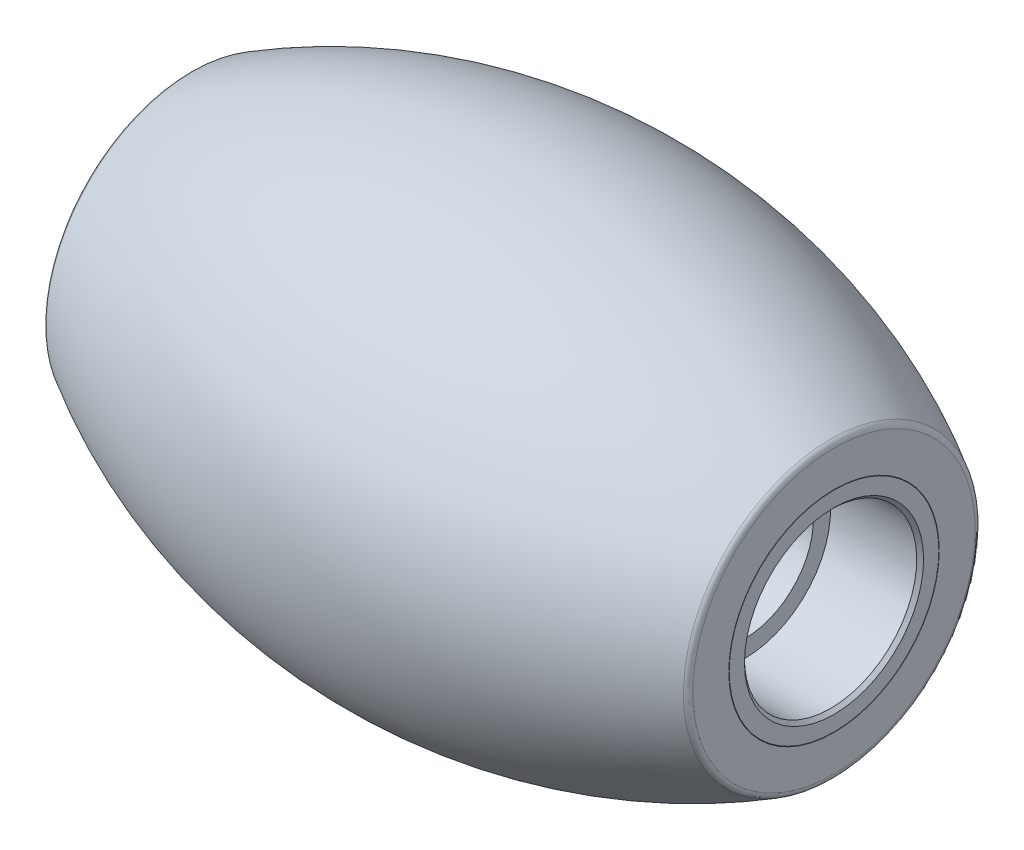
SolidWorks part; units mm, degrees
ref_plane "Face" through (0, 0, 0) normal (0, 0, 1) x (1, 0, 0)
ref_plane "Dessus" through (0, 0, 0) normal (0, 1, 0) x (1, 0, 0)
ref_plane "Droite" through (0, 0, 0) normal (1, 0, 0) x (0, 0, -1)
sketch "Esquisse1" plane through (0, 0, 0) normal (0, 0, 1) x (1, 0, 0)
  line L0 (-9.35, 0) -> (9.35, 0) construction
  line L1 (9.35, 0) -> (9.35, 3.0428)
  line L2 (-9.35, 3.0428) -> (-9.35, 0)
  line L3 (0, 0) -> (0, 5.75) construction
  line L4 (-9.35, 0) -> (9.35, 0)
  arc A0 (-9.35, 3.0428) -> (9.35, 3.0428) centre (0, -11.75) cw
  dimension "D1" = 11.5
  dimension "D3" = 17.5
  dimension "D2" = 18.7
revolve "Révolution1" add sketch "Esquisse1" angle 360 about L4
sketch "Esquisse2" plane through (0, 0, 0) normal (0, 0, 1) x (1, 0, 0)
  line L0 (-9.35, 2.5) -> (-6.75, 2.5)
  line L1 (-9.35, 3.0428) -> (-9.35, -3.0428) construction
  line L2 (-6.75, 2.5) -> (-6.75, 2)
  line L3 (-6.75, 2) -> (6.75, 2)
  line L4 (6.75, 2) -> (6.75, 2.5)
  line L5 (6.75, 2.5) -> (9.35, 2.5)
  line L6 (9.35, -3.0428) -> (9.35, 3.0428) construction
  line L7 (-9.35, 0) -> (9.35, 0) construction
  line L8 (-9.35, 2.5) -> (-9.35, 0)
  line L9 (9.35, 2.5) -> (9.35, 0)
  line L10 (-9.35, 0) -> (9.35, 0)
  dimension "D1" = 5
  dimension "D2" = 2.6
  dimension "D3" = 4
revolve "Enlèvement de matière-Révolution1" cut sketch "Esquisse2" angle 360 about L7
chamfer "Chanfrein1" distance 0.1 angle 45 2 edges at (-9.35, -2.5, 0) (9.35, -2.5, 0)
sketch "Esquisse4" plane through (0, 0, 0) normal (0, 0, 1) x (1, 0, 0)
  line L0 (-9.35, 3.0546) -> (-9.35, 4.2133)
  line L1 (9.35, 3.0546) -> (9.35, 4.2133)
  line L2 (-9.35, 0) -> (9.35, 0) construction
  line L3 (-9.35, 2.6) -> (-9.35, -2.6) construction
  line L4 (9.35, -2.6) -> (9.35, 2.6) construction
  line L5 (0, 0) -> (0, 6.75) construction
  arc A0 (9.35, 3.0428) -> (-9.35, 3.0428) centre (0, -11.75) ccw
  arc A1 (-9.35, -3.0428) -> (9.35, -3.0428) centre (0, 11.75) ccw
  arc A2 (-9.35, -3.0428) -> (9.35, -3.0428) centre (0, 11.75) ccw construction
  arc A3 (9.35, 3.0428) -> (-9.35, 3.0428) centre (0, -11.75) ccw construction
  arc A4 (9.35, 4.2133) -> (-9.35, 4.2133) centre (0, -11.75) ccw
  arc A5 (9.35, 3.0546) -> (-9.35, 3.0546) centre (0, -11.75) ccw
  arc A7 (9.3553, 3.0513) -> (-9.3553, 3.0513) centre (0, -11.75) ccw construction
  arc A8 (9.8843, 3.8881) -> (-9.8843, 3.8881) centre (0, -11.75) ccw construction
  dimension "D3" = 18.5
  dimension "D4" = 6.75
  dimension "D1" = 1
  dimension "D2" = 0.01
revolve "Révolution2" add sketch "Esquisse4" angle 360 about L2
fillet "Congé1" radius 0.2 2 edges at (-9.35, -4.2133, 0) (9.35, -4.2133, 0)
